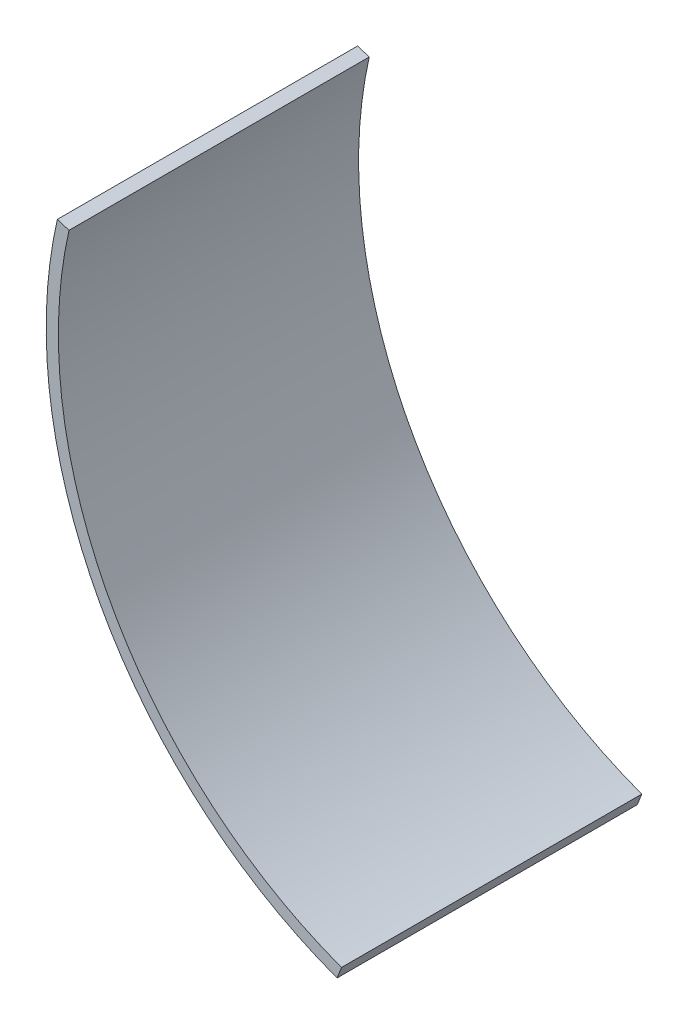
SolidWorks part; units mm, degrees
material "AISI 1020"
ref_plane "Ön Düzlem" through (0, 0, 0) normal (0, 0, 1) x (1, 0, 0)
ref_plane "Üst Düzlem" through (0, 0, 0) normal (0, 1, 0) x (1, 0, 0)
ref_plane "Sağ Düzlem" through (0, 0, 0) normal (1, 0, 0) x (0, 0, -1)
sketch "Model" plane through (0, 0, 0) normal (0, 0, 1) x (1, 0, 0)
  line L0 (3052.5593, 1293.1262) -> (3057.9972, 1307.108)
  line L1 (2707.2752, 1930.5821) -> (2722.1639, 1925.8852)
  arc A0 (2707.81, 1930.4134) -> (3052.5593, 1293.1262) centre (3243.4508, 1808.2837) ccw
  arc A1 (2722.1639, 1925.8852) -> (3057.9972, 1307.108) centre (3243.4508, 1808.2837) ccw
extrude "Yükseklik-Ekstrüzyon1" add sketch "Model" along normal blind 370 contours A1 L1 A0 L0
